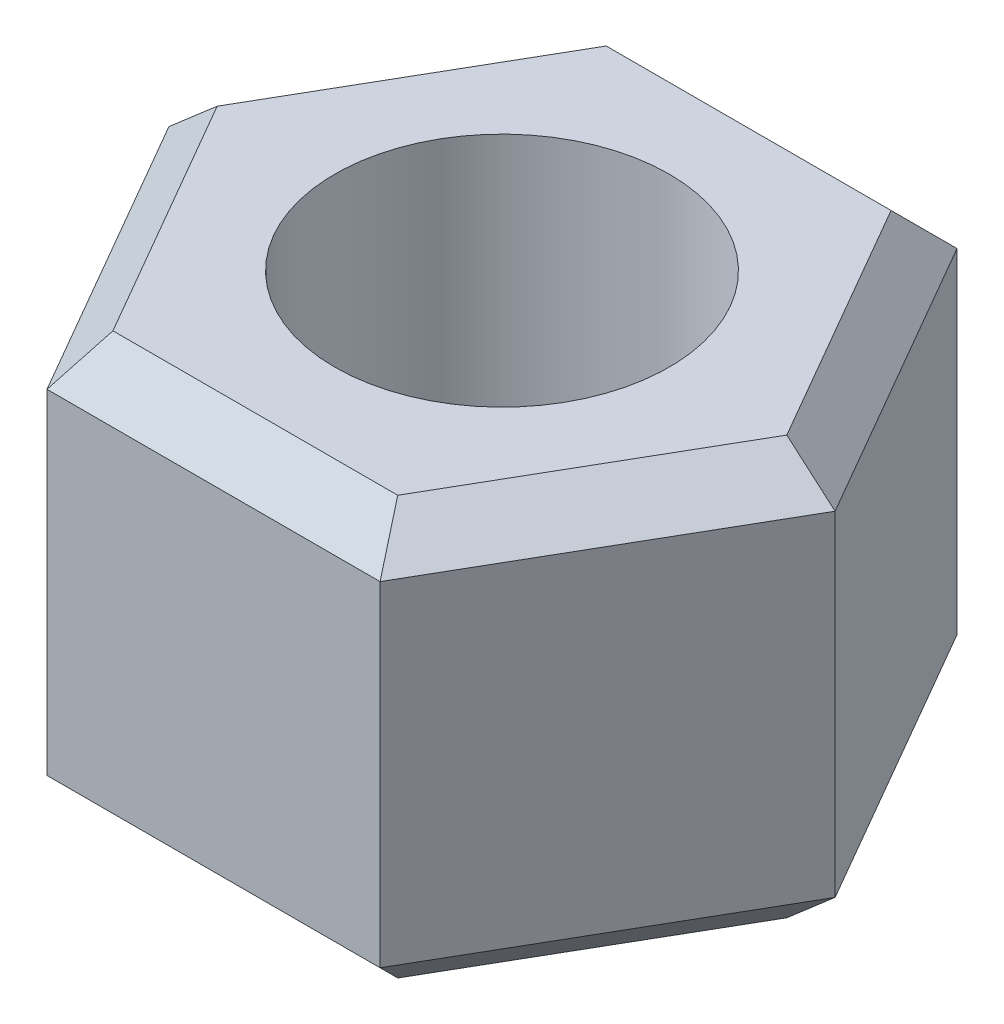
SolidWorks part; units mm, degrees
ref_plane "前视基准面" through (0, 0, 0) normal (0, 0, 1) x (1, 0, 0)
ref_plane "上视基准面" through (0, 0, 0) normal (0, 1, 0) x (1, 0, 0)
ref_plane "右视基准面" through (0, 0, 0) normal (1, 0, 0) x (0, 0, -1)
sketch "草图1" plane through (0, 0, 0) normal (0, 1, 0) x (1, 0, 0)
  line L1 (-3.9837, 0) -> (-1.9919, -3.45)
  line L2 (-1.9919, -3.45) -> (1.9919, -3.45)
  line L3 (1.9919, -3.45) -> (3.9837, 0)
  line L4 (3.9837, 0) -> (1.9919, 3.45)
  line L5 (1.9919, 3.45) -> (-1.9919, 3.45)
  line L6 (-1.9919, 3.45) -> (-3.9837, 0)
  circle A0 centre (0, 0) radius 2
  circle A1 centre (0, 0) radius 3.45 construction
extrude "凸台-拉伸1" add sketch "草图1" along normal blind 5
chamfer "倒角1" distance 0.5 angle 45 12 edges at (-2.9878, 0, 1.725) (0, 0, 3.45) (2.9878, 0, 1.725) (2.9878, 0, -1.725) (0, 0, -3.45) (-2.9878, 0, -1.725) (0, 5, -3.45) (2.9878, 5, -1.725) (2.9878, 5, 1.725) (0, 5, 3.45) (-2.9878, 5, 1.725) (-2.9878, 5, -1.725)
